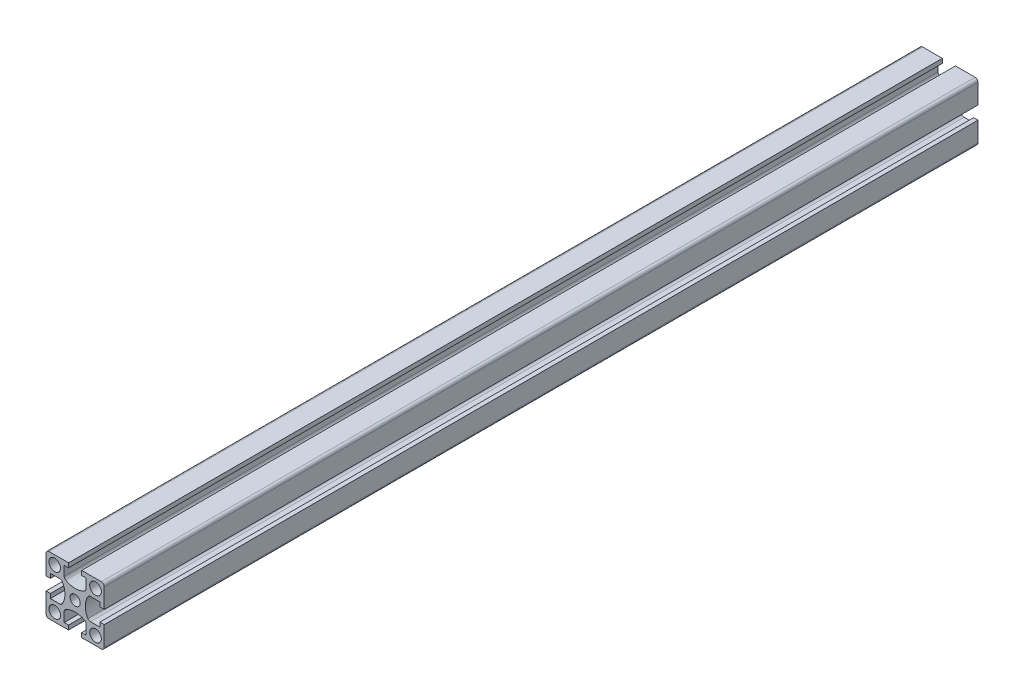
SolidWorks part; units mm, degrees
ref_plane "Front Plane" through (0, 0, 0) normal (0, 0, 1) x (1, 0, 0)
ref_plane "Top Plane" through (0, 0, 0) normal (0, 1, 0) x (1, 0, 0)
ref_plane "Right Plane" through (0, 0, 0) normal (1, 0, 0) x (0, 0, -1)
sketch "Sketch1" plane through (0, 0, 0) normal (0, 0, 1) x (1, 0, 0)
  line L64 (-10, 9) -> (-10, 2.25)
  line L65 (-10, 2.25) -> (-8.5, 2.25)
  line L66 (-8.5, 2.25) -> (-8.5, 3.75)
  line L67 (-8.5, 3.75) -> (-5.2369, 3.75)
  line L68 (-5.2369, -3.75) -> (-8.5, -3.75)
  line L69 (-8.5, -3.75) -> (-8.5, -2.25)
  line L70 (-8.5, -2.25) -> (-10, -2.25)
  line L71 (-10, -2.25) -> (-10, -9)
  line L72 (-9, -10) -> (-2.25, -10)
  line L73 (-2.25, -10) -> (-2.25, -8.5)
  line L74 (-2.25, -8.5) -> (-3.75, -8.5)
  line L75 (-3.75, -8.5) -> (-3.75, -5.2369)
  line L76 (3.75, -5.2369) -> (3.75, -8.5)
  line L77 (3.75, -8.5) -> (2.25, -8.5)
  line L78 (2.25, -8.5) -> (2.25, -10)
  line L79 (2.25, -10) -> (9, -10)
  line L80 (10, -9) -> (10, -2.25)
  line L81 (10, -2.25) -> (8.5, -2.25)
  line L82 (8.5, -2.25) -> (8.5, -3.75)
  line L83 (8.5, -3.75) -> (5.2369, -3.75)
  line L84 (5.2369, 3.75) -> (8.5, 3.75)
  line L85 (8.5, 3.75) -> (8.5, 2.25)
  line L86 (8.5, 2.25) -> (10, 2.25)
  line L87 (10, 2.25) -> (10, 9)
  line L88 (9, 10) -> (2.25, 10)
  line L89 (2.25, 10) -> (2.25, 8.5)
  line L90 (2.25, 8.5) -> (3.75, 8.5)
  line L91 (3.75, 8.5) -> (3.75, 5.2369)
  line L92 (-3.75, 5.2369) -> (-3.75, 8.5)
  line L93 (-3.75, 8.5) -> (-2.25, 8.5)
  line L94 (-2.25, 8.5) -> (-2.25, 10)
  line L95 (-2.25, 10) -> (-9, 10)
  circle A5 centre (-7, -7) radius 2
  circle A6 centre (7, -7) radius 2
  circle A7 centre (7, 7) radius 2
  circle A8 centre (0, 0) radius 1.75
  circle A9 centre (-7, 7) radius 2
  arc A32 (-9, 10) -> (-10, 9) centre (-9, 9) ccw
  arc A33 (-4.3708, 3.25) -> (-5.2369, 3.75) centre (-5.2369, 2.75) ccw
  arc A34 (-4.3708, -3.25) -> (-4.3708, 3.25) centre (-10, 0) ccw
  arc A35 (-5.2369, -3.75) -> (-4.3708, -3.25) centre (-5.2369, -2.75) ccw
  arc A36 (-10, -9) -> (-9, -10) centre (-9, -9) ccw
  arc A37 (-3.25, -4.3708) -> (-3.75, -5.2369) centre (-2.75, -5.2369) ccw
  arc A38 (3.25, -4.3708) -> (-3.25, -4.3708) centre (0, -10) ccw
  arc A39 (3.75, -5.2369) -> (3.25, -4.3708) centre (2.75, -5.2369) ccw
  arc A40 (9, -10) -> (10, -9) centre (9, -9) ccw
  arc A41 (4.3708, -3.25) -> (5.2369, -3.75) centre (5.2369, -2.75) ccw
  arc A42 (4.3708, 3.25) -> (4.3708, -3.25) centre (10, 0) ccw
  arc A43 (5.2369, 3.75) -> (4.3708, 3.25) centre (5.2369, 2.75) ccw
  arc A44 (10, 9) -> (9, 10) centre (9, 9) ccw
  arc A45 (3.25, 4.3708) -> (3.75, 5.2369) centre (2.75, 5.2369) ccw
  arc A46 (-3.25, 4.3708) -> (3.25, 4.3708) centre (0, 10) ccw
  arc A47 (-3.75, 5.2369) -> (-3.25, 4.3708) centre (-2.75, 5.2369) ccw
extrude "Boss-Extrude1" add sketch "Sketch1" along normal blind 300
